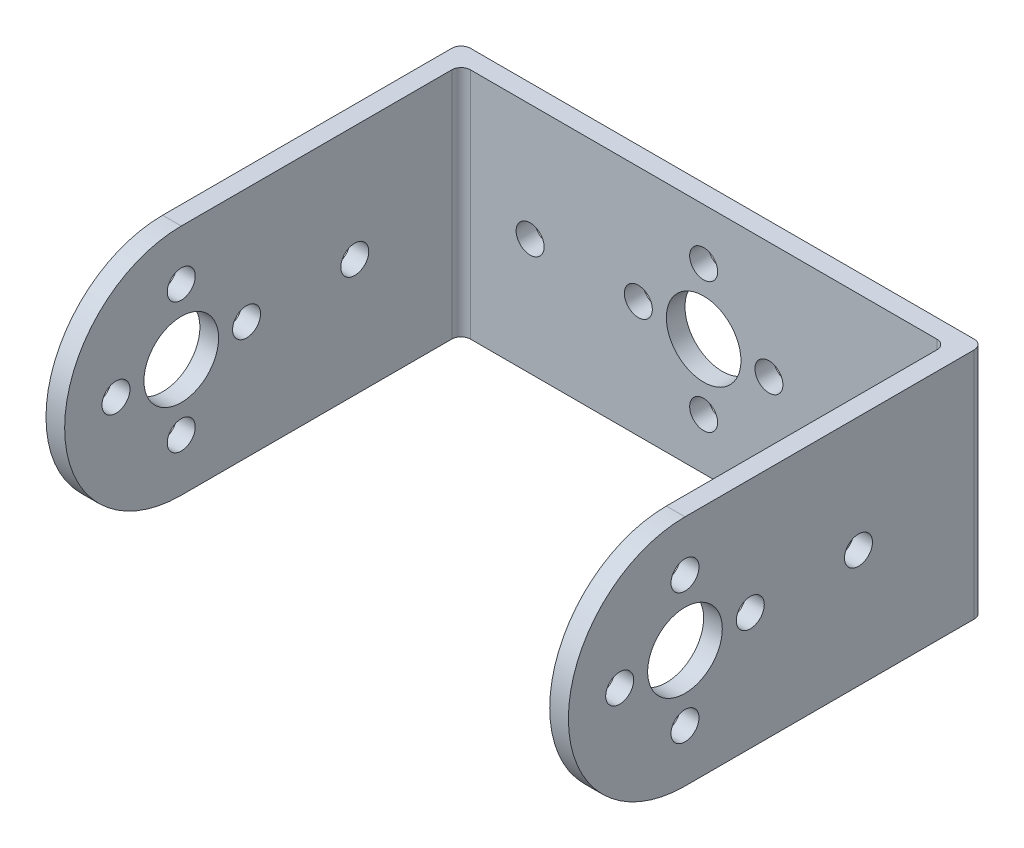
SolidWorks part; units mm, degrees
ref_plane "前视基准面" through (0, 0, 0) normal (0, 0, 1) x (1, 0, 0)
ref_plane "上视基准面" through (0, 0, 0) normal (0, 1, 0) x (1, 0, 0)
ref_plane "右视基准面" through (0, 0, 0) normal (1, 0, 0) x (0, 0, -1)
sketch "草图1" plane through (0, 0, 0) normal (0, 0, 1) x (1, 0, 0)
  line L1 (-28, 12.5) -> (28, 12.5)
  line L2 (-28, 12.5) -> (-28, -12.5)
  line L3 (-28, -12.5) -> (28, -12.5)
  line L4 (28, 12.5) -> (28, -12.5)
  line L5 (-28, 12.5) -> (28, -12.5) construction
  line L6 (-28, -12.5) -> (28, 12.5) construction
  point P0 (0, 0)
  dimension "D1" = 56
  dimension "D2" = 25
extrude "凸台-拉伸1" add sketch "草图1" along normal blind 44.5
sketch "草图2" plane through (0, -12.5, 0) normal (0, -1, 0) x (1, 0, 0)
  line L0 (0, 45.8587) -> (0, -3.5149) construction
  line L1 (-28, 44.5) -> (28, 44.5) construction
  line L2 (0, 44.5) -> (26, 44.5)
  line L3 (26, 44.5) -> (26, 2)
  line L4 (26, 2) -> (-26, 2)
  line L5 (-26, 2) -> (-26, 44.5)
  line L6 (0, 44.5) -> (-26, 44.5)
  point P3 (0, 44.5)
  point P13 (-28, 44.5)
extrude "切除-拉伸1" cut sketch "草图2" against normal through all
sketch "草图3" plane through (28, 0, 0) normal (1, 0, 0) x (0, 0, -1)
  line L0 (-32, 12.5) -> (-44.5, 12.5)
  line L1 (-44.5, 12.5) -> (-44.5, -12.5)
  line L2 (-44.5, 12.5) -> (0, 12.5) construction
  line L3 (-44.5, -12.5) -> (0, -12.5) construction
  line L4 (-44.5, -12.5) -> (-32, -12.5)
  arc A0 (-32, 12.5) -> (-32, -12.5) centre (-32, 0) ccw
  line M4 (0, 12.5) -> (-44.5, 12.5)
  line M5 (-44.5, 12.5) -> (-44.5, -12.5)
  line M6 (-44.5, -12.5) -> (0, -12.5)
extrude "切除-拉伸2" cut sketch "草图3" against normal through all contours A0 M4 M5 | A0 L1 M6
sketch "草图4" plane through (0, 0, 2) normal (0, 0, 1) x (1, 0, 0)
  line L0 (-32.0699, 0) -> (34.4869, 0) construction
  line L1 (0, 16.1115) -> (0, -17.9038) construction
  circle A0 centre (0, 0) radius 4
  circle A1 centre (0, 0) radius 7 construction
  circle A2 centre (0, 7) radius 1.5
  circle A3 centre (0, -7) radius 1.5
  circle A4 centre (-7, 0) radius 1.5
  circle A5 centre (7, 0) radius 1.5
  circle A6 centre (18.6, 0) radius 1.5
  circle A7 centre (-18.6, 0) radius 1.5
  dimension "D1" = 18.6
extrude "切除-拉伸3" cut sketch "草图4" against normal through all
sketch "草图5" plane through (28, 0, 0) normal (1, 0, 0) x (0, 0, -1)
  circle A0 centre (-32, 0.1083) radius 4
  circle A1 centre (-32, 0.1083) radius 7 construction
  circle A2 centre (-32, 7.1083) radius 1.5
  circle A3 centre (-39, 0.1083) radius 1.5
  circle A4 centre (-32, -6.8917) radius 1.5
  circle A5 centre (-25, 0.1083) radius 1.5
  circle A6 centre (-13.4, 0.1083) radius 1.5
extrude "切除-拉伸4" cut sketch "草图5" against normal through all
fillet "圆角1" radius 1 4 edges at (-28, 0, 0) (28, 0, 0) (26, 0, 2) (-26, 0, 2)
